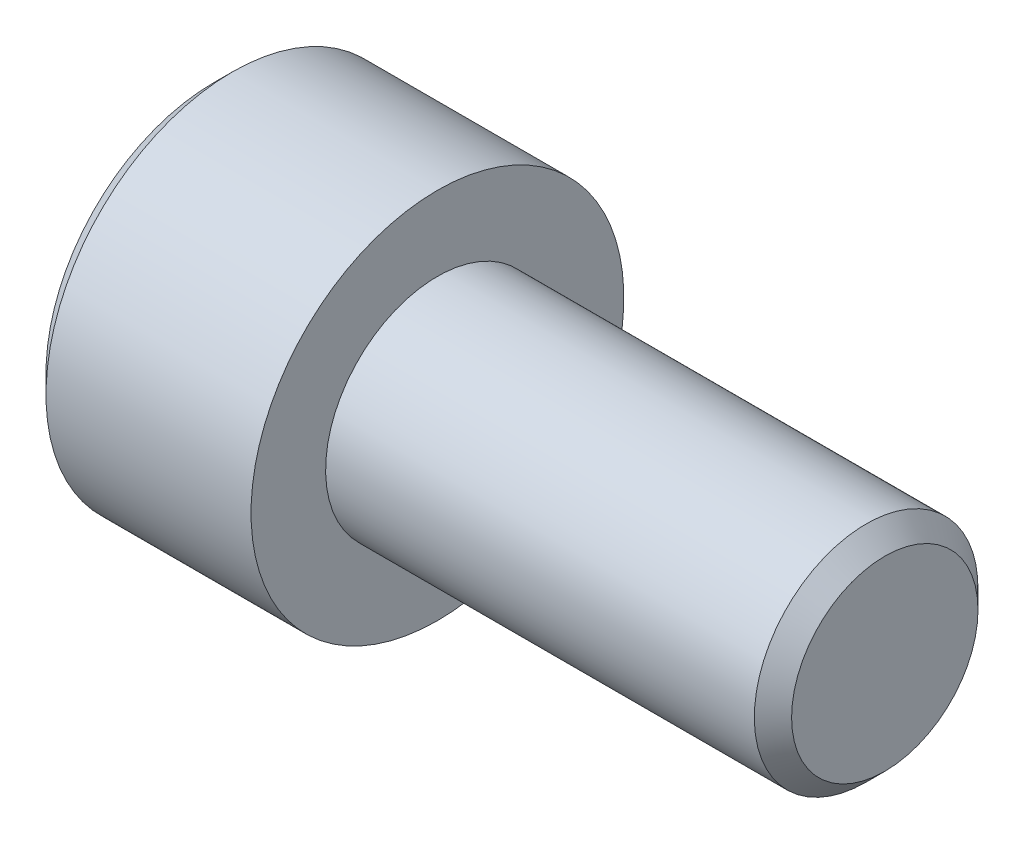
SolidWorks part; units mm, degrees
ref_plane "Front" through (0, 0, 0) normal (0, 0, 1) x (1, 0, 0)
ref_plane "Top" through (0, 0, 0) normal (0, 1, 0) x (1, 0, 0)
ref_plane "Right" through (0, 0, 0) normal (1, 0, 0) x (0, 0, -1)
sketch "Sketch1" plane through (0, 0, 0) normal (0, 0, 1) x (1, 0, 0)
  line L0 (-6, 0) -> (-6, 5)
  line L1 (-6, 0) -> (12, 0)
  line L2 (-6, 5) -> (0, 5)
  line L3 (0, 5) -> (0, 3)
  line L4 (0, 3) -> (12, 3)
  line L6 (12, 3) -> (12, 0)
  line L8 (12, 0) -> (-6, 0) construction
  dimension "D1" = 6
  dimension "D2" = 10
  dimension "D3" = 6
  dimension "D4" = 12
revolve "Revolve1" add sketch "Sketch1" angle 360 about L8
sketch "Sketch2" plane through (0, 0, 0) normal (0, 0, 1) x (1, 0, 0)
  line L0 (-6, 0) -> (-6, 2.495)
  line L1 (-6, 2.495) -> (-3, 2.495)
  line L2 (-3, 2.495) -> (-2.3315, 0)
  line L3 (-6, 0) -> (-2.3315, 0)
  line L4 (-2.3315, 0) -> (-6, 0) construction
  line L6 (-6, 5) -> (-6, -5) construction
  dimension "D1" = 4.99
  dimension "D2" = 75
  dimension "D3" = 3
revolve "Cut-Revolve1" cut sketch "Sketch2" angle 360 about L4
sketch "Sketch3" plane through (-6, 0, 0) normal (-1, 0, 0) x (0, 0, 1)
  line L1 (0, 2.8868) -> (-2.5, 1.4434)
  line L2 (-2.5, 1.4434) -> (-2.5, -1.4434)
  line L3 (-2.5, -1.4434) -> (0, -2.8868)
  line L4 (0, -2.8868) -> (2.5, -1.4434)
  line L5 (2.5, -1.4434) -> (2.5, 1.4434)
  line L6 (2.5, 1.4434) -> (0, 2.8868)
  circle A0 centre (0, 0) radius 2.5 construction
  dimension "D1" = 5
extrude "Cut-Extrude1" cut sketch "Sketch3" against normal blind 3
chamfer "Chamfer1" distance 0.5 angle 45 2 edges at (12, -3, 0) (-6, -5, 0)
